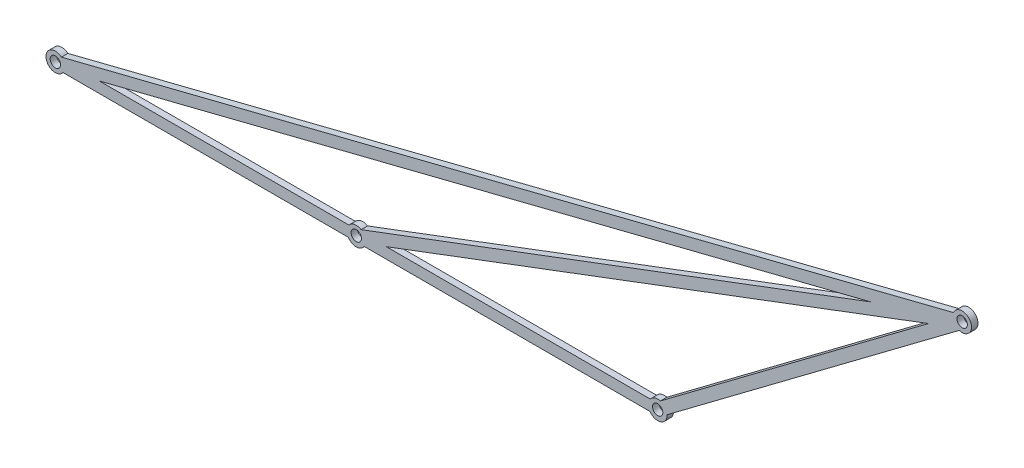
SolidWorks part; units mm, degrees
material "AISI 1020"
ref_plane "Front Plane" through (0, 0, 0) normal (0, 0, 1) x (1, 0, 0)
ref_plane "Top Plane" through (0, 0, 0) normal (0, 1, 0) x (1, 0, 0)
ref_plane "Right Plane" through (0, 0, 0) normal (1, 0, 0) x (0, 0, -1)
sketch "Sketch1" plane through (0, 0, 0) normal (0, 0, 1) x (1, 0, 0)
  line L0 (0, 0) -> (400, 300) construction
  line L1 (400, 300) -> (-790.5974, 0) construction
  line L2 (-790.5974, 0) -> (0, 0) construction
  line L3 (400, 300) -> (-395.2987, 0) construction
  line L4 (0, -7.1494) -> (-790.5974, -7.1494)
  line L5 (0, -7.1494) -> (0, 7.1494)
  line L6 (-790.5974, -7.1494) -> (-790.5974, 7.1494)
  line L7 (0, 7.1494) -> (-790.5974, 7.1494)
  line L8 (0, -7.1494) -> (-790.5974, 7.1494) construction
  line L9 (-790.5974, -7.1494) -> (0, 7.1494) construction
  line L10 (-779.1536, -4.4893) -> (400.1325, 292.6605)
  line L11 (-779.1536, -4.4893) -> (-782.6473, 9.3761)
  line L12 (400.1325, 292.6605) -> (396.6387, 306.5259)
  line L13 (-782.6473, 9.3761) -> (396.6387, 306.5259)
  line L14 (-779.1536, -4.4893) -> (396.6387, 306.5259) construction
  line L15 (400.1325, 292.6605) -> (-782.6473, 9.3761) construction
  line L16 (397.4767, 306.6893) -> (-397.822, 6.6893)
  line L17 (397.4767, 306.6893) -> (402.5233, 293.3107)
  line L18 (-397.822, 6.6893) -> (-392.7754, -6.6893)
  line L19 (402.5233, 293.3107) -> (-392.7754, -6.6893)
  line L20 (397.4767, 306.6893) -> (-392.7754, -6.6893) construction
  line L21 (-397.822, 6.6893) -> (402.5233, 293.3107) construction
  line L22 (-4.2896, 5.7195) -> (395.7104, 305.7195)
  line L23 (-4.2896, 5.7195) -> (4.2896, -5.7195)
  line L24 (395.7104, 305.7195) -> (404.2896, 294.2805)
  line L25 (4.2896, -5.7195) -> (404.2896, 294.2805)
  line L26 (-4.2896, 5.7195) -> (404.2896, 294.2805) construction
  line L27 (395.7104, 305.7195) -> (4.2896, -5.7195) construction
  circle A2 centre (-790.5974, 0) radius 12.2928
  circle A3 centre (-395.6728, -0.5829) radius 12.2928
  circle A5 centre (0.1563, -0.2382) radius 12.2928
  circle A6 centre (399.723, 299.7489) radius 12.2928
  point P5 (0, 0)
  point P6 (-191.2574, 151.0183)
  point P11 (2.3507, 150)
  point P12 (200, 150)
  point P21 (0, 0)
  point P27 (0, 0)
  dimension "D1" = 850
  dimension "D2" = 395.2987
  dimension "D3" = 395.2987
  dimension "D4" = 300
  dimension "D5" = 500
  dimension "D6" = 1227.8119
  dimension "D7" = 400
  dimension "D8" = 14.2988
  dimension "D9" = 14.2988
  dimension "D10" = 14.2988
  dimension "D11" = 14.2988
extrude "Boss-Extrude3" add sketch "Sketch1" along normal blind 8.5 contours L25 A6 L13 L12 L16 L17 L24 | L7 L6 L4 L5 | A3 | A5 | A2
sketch "Sketch2" plane through (0, 0, 8.5) normal (0, 0, 1) x (1, 0, 0)
  circle A2 centre (0, 0) radius 6.815
  circle A3 centre (399.723, 299.7489) radius 6.815
  circle A4 centre (-395.6095, 0) radius 6.815
  circle A5 centre (-790.5974, 0) radius 6.815
  dimension "D1" = 13.63
  dimension "D2" = 13.63
  dimension "D3" = 13.63
  dimension "D4" = 13.63
extrude "Cut-Extrude1" cut sketch "Sketch2" against normal through all
